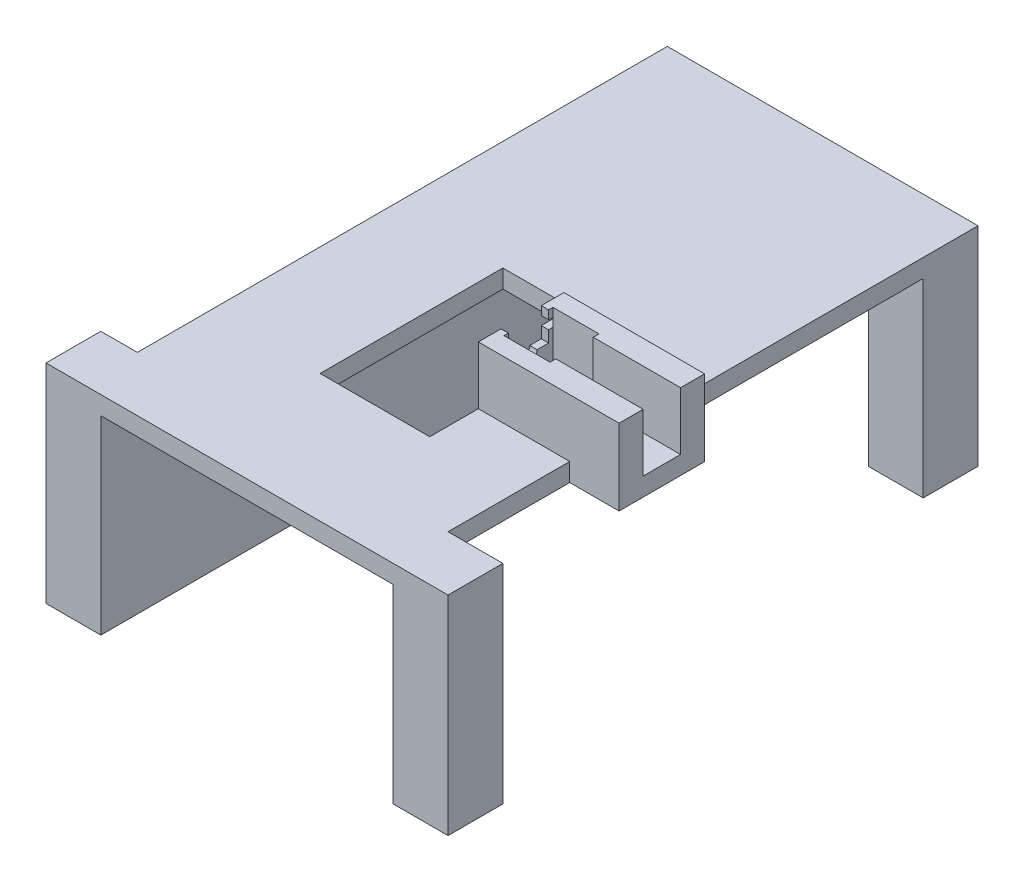
SolidWorks part; units mm, degrees
ref_plane "Front Plane" through (0, 0, 0) normal (0, 0, 1) x (1, 0, 0)
ref_plane "Top Plane" through (0, 0, 0) normal (0, 1, 0) x (1, 0, 0)
ref_plane "Right Plane" through (0, 0, 0) normal (1, 0, 0) x (0, 0, -1)
sketch "Sketch1" plane through (0, 0, 0) normal (0, 1, 0) x (1, 0, 0)
  line L1 (-50.8, -76.2) -> (50.8, -76.2)
  line L2 (-50.8, -76.2) -> (-50.8, 76.2)
  line L3 (-50.8, 76.2) -> (50.8, 76.2)
  line L4 (50.8, -76.2) -> (50.8, 76.2)
  line L5 (-50.8, -76.2) -> (50.8, 76.2) construction
  line L6 (-50.8, 76.2) -> (50.8, -76.2) construction
  point P0 (0, 0)
  dimension "D1" = 152.4
  dimension "D2" = 101.6
extrude "Boss-Extrude1" add sketch "Sketch1" against normal blind 6.35
sketch "Sketch2" plane through (0, 0, 0) normal (0, 1, 0) x (1, 0, 0)
  line L1 (-19.05, -31.75) -> (19.05, -31.75)
  line L2 (-19.05, -31.75) -> (-19.05, 31.75)
  line L3 (-19.05, 31.75) -> (19.05, 31.75)
  line L4 (19.05, -31.75) -> (19.05, 31.75)
  line L5 (-19.05, -31.75) -> (19.05, 31.75) construction
  line L6 (-19.05, 31.75) -> (19.05, -31.75) construction
  point P0 (0, 0)
  dimension "D1" = 38.1
  dimension "D2" = 63.5
extrude "Cut-Extrude1" cut sketch "Sketch2" against normal through all
sketch "Sketch4" plane through (0, 0, 0) normal (0, 1, 0) x (1, 0, 0)
  line L0 (19.05, -31.75) -> (19.05, 31.75) construction
  line L1 (21.59, -8.509) -> (50.8, -8.509)
  line L3 (21.59, 8.509) -> (50.8, 8.509)
  line L4 (50.8, -8.509) -> (50.8, 8.509)
  line L5 (21.59, -8.509) -> (50.8, 8.509) construction
  line L6 (50.8, -8.509) -> (21.59, 8.509) construction
  line L7 (50.8, -76.2) -> (50.8, 76.2) construction
  line L9 (19.05, 14.859) -> (19.05, -14.859)
  line L10 (19.05, 14.859) -> (50.8, 14.859)
  line L11 (50.8, 14.859) -> (50.8, 8.509)
  line L12 (21.59, 8.509) -> (21.59, -8.509)
  line L13 (50.8, 8.509) -> (61.595, 8.509)
  line L14 (19.05, -14.859) -> (50.8, -14.859)
  line L15 (61.595, 8.509) -> (61.595, -8.509)
  line L16 (61.595, -8.509) -> (50.8, -8.509)
  line L17 (50.8, 14.859) -> (67.945, 14.859)
  line L18 (67.945, 14.859) -> (67.945, -14.859)
  line L19 (67.945, -14.859) -> (50.8, -14.859)
  point P0 (19.05, 0)
  point P2 (36.195, 0)
  line M13 (19.05, 31.75) -> (19.05, -31.75)
  line M16 (50.8, -76.2) -> (50.8, 76.2)
  dimension "D1" = 17.018
  dimension "D2" = 6.35
  dimension "D3" = 6.35
  dimension "D4" = 2.54
  dimension "D5" = 40.005
  dimension "D6" = 6.35
extrude "Boss-Extrude3" add sketch "Sketch4" against normal through all and the other way blind 10.0965 contours L19 L18 L17 L13 L15 L16 M16 | L14 L1 L12 L3 L10 M13 M16
sketch "Sketch6" plane through (19.05, 0, 0) normal (-1, 0, 0) x (0, 0, 1)
  line L0 (-14.859, 10.0965) -> (14.859, 10.0965) construction
  circle A0 centre (0, 10.0965) radius 3
  dimension "D1" = 6
extrude "Cut-Extrude2" cut sketch "Sketch6" against normal up to next
sketch "Sketch7" plane through (0, 10.0965, 0) normal (0, 1, 0) x (1, 0, 0)
  line L0 (21.59, 8.509) -> (37.59, 8.509) construction
  line L1 (21.59, 8.509) -> (61.595, 8.509) construction
  line L2 (37.59, 8.509) -> (37.59, 6.5)
  line L3 (37.59, 6.5) -> (61.595, 6.5)
  line L4 (61.595, 8.509) -> (61.595, -8.509) construction
  line L5 (61.595, 6.5) -> (61.595, -6.5)
  line L6 (61.595, -6.5) -> (37.59, -6.5)
  line L7 (37.59, -6.5) -> (37.59, -8.509)
  line L8 (61.595, -8.509) -> (21.59, -8.509) construction
  line L9 (37.59, -8.509) -> (61.595, -8.509)
  line L10 (61.595, -8.509) -> (61.595, -6.5)
  line L11 (61.595, 6.5) -> (61.595, 8.509)
  line L12 (61.595, 8.509) -> (37.59, 8.509)
  line L13 (21.59, 8.509) -> (21.59, 3) construction
  line M8 (21.59, 8.509) -> (61.595, 8.509)
  line M9 (61.595, 8.509) -> (61.595, -8.509)
  dimension "D1" = 13
  dimension "D2" = 16
  dimension "D3" = 24.005
extrude "Boss-Extrude4" add sketch "Sketch7" against normal through all contours L2 L3 M9 M8 | L6 L7 L9 L10
sketch "Sketch10" plane through (50.8, 0, 0) normal (1, 0, 0) x (0, 0, -1)
  line L1 (-6.5, -6.35) -> (6.5, -6.35)
  line L2 (-6.5, -6.35) -> (-6.5, 0)
  line L3 (-6.5, 0) -> (6.5, 0)
  line L4 (6.5, -6.35) -> (6.5, 0)
extrude "Boss-Extrude5" add sketch "Sketch10" along normal through all
sketch "Sketch11" plane through (61.595, 0, 0) normal (-1, 0, 0) x (0, 0, 1)
  line L1 (6.5, 0) -> (-6.5, 0)
  line L2 (6.5, 0) -> (6.5, 10.0965)
  line L3 (6.5, 10.0965) -> (-6.5, 10.0965)
  line L4 (-6.5, 0) -> (-6.5, 10.0965)
extrude "Cut-Extrude3" cut sketch "Sketch11" against normal up to next
sketch "Sketch12" plane through (0, 10.0965, 0) normal (0, 1, 0) x (1, 0, 0)
  line L0 (67.945, -14.859) -> (67.945, -6.5) construction
  line L1 (67.945, -6.5) -> (37.59, -6.5) construction
  line L2 (37.59, -6.5) -> (37.59, -8.509) construction
  line L3 (37.59, -8.509) -> (21.59, -8.509) construction
  line L4 (21.59, -8.509) -> (21.59, -3) construction
  line L5 (21.59, -3) -> (19.05, -3) construction
  line L6 (19.05, -3) -> (19.05, -14.859) construction
  line L7 (19.05, -14.859) -> (67.945, -14.859) construction
  line L8 (37.59, 6.5) -> (67.945, 6.5) construction
  line L9 (67.945, 6.5) -> (67.945, 14.859) construction
  line L10 (67.945, 14.859) -> (19.05, 14.859) construction
  line L11 (19.05, 14.859) -> (19.05, 3) construction
  line L12 (19.05, 3) -> (21.59, 3) construction
  line L13 (21.59, 3) -> (21.59, 8.509) construction
  line L14 (21.59, 8.509) -> (37.59, 8.509) construction
  line L15 (37.59, 8.509) -> (37.59, 6.5) construction
  line L16 (67.945, -14.859) -> (67.945, -6.5)
  line L17 (67.945, -6.5) -> (37.59, -6.5)
  line L18 (37.59, -6.5) -> (37.59, -8.509)
  line L19 (37.59, -8.509) -> (21.59, -8.509)
  line L20 (21.59, -8.509) -> (21.59, -3)
  line L21 (21.59, -3) -> (19.05, -3)
  line L22 (19.05, -3) -> (19.05, -14.859)
  line L23 (19.05, -14.859) -> (67.945, -14.859)
  line L24 (37.59, 6.5) -> (67.945, 6.5)
  line L25 (67.945, 6.5) -> (67.945, 14.859)
  line L26 (67.945, 14.859) -> (19.05, 14.859)
  line L27 (19.05, 14.859) -> (19.05, 3)
  line L28 (19.05, 3) -> (21.59, 3)
  line L29 (21.59, 3) -> (21.59, 8.509)
  line L30 (21.59, 8.509) -> (37.59, 8.509)
  line L31 (37.59, 8.509) -> (37.59, 6.5)
extrude "Boss-Extrude6" add sketch "Sketch12" along normal blind 10
sketch "Sketch13" plane through (19.05, 0, 0) normal (-1, 0, 0) x (0, 0, 1)
  line L0 (3, 10.0965) -> (7, 10.0965)
  line L1 (7, 10.0965) -> (7, 14.0965)
  line L2 (7, 14.0965) -> (11, 14.0965)
  line L3 (11, 14.0965) -> (11, 17.0965)
  line L4 (11, 17.0965) -> (7, 17.0965)
  line L5 (7, 17.0965) -> (7, 20.0965)
  line L6 (3, 20.0965) -> (14.859, 20.0965) construction
  line L7 (7, 20.0965) -> (3, 20.0965)
  line L8 (3, 20.0965) -> (3, 10.0965)
  arc A0 (-3, 10.0965) -> (3, 10.0965) centre (0, 10.0965) ccw construction
  arc A1 (-3, 10.0965) -> (3, 10.0965) centre (0, 10.0965) ccw construction
  dimension "D1" = 4
  dimension "D2" = 4
  dimension "D3" = 3
  dimension "D4" = 4
extrude "Cut-Extrude4" cut sketch "Sketch13" against normal up to surface (2.54 mm away) up to face at (21.59, 12.1974, 0)
mirror "Mirror1" about plane through (0, 0, 0) normal (0, 0, 1) of "Cut-Extrude4"
sketch "Sketch14" plane through (0, 0, -76.2) normal (0, 0, -1) x (-1, 0, 0)
  line L4 (50.8, 0) -> (-50.8, 0)
  line L5 (-50.8, 0) -> (-50.8, -6.35)
  line L6 (-50.8, -6.35) -> (50.8, -6.35)
  line L7 (50.8, -6.35) -> (50.8, 0)
  line L8 (50.8, 0) -> (-50.8, 0)
  line L9 (-50.8, 0) -> (-50.8, -6.35)
  line L10 (-50.8, -6.35) -> (50.8, -6.35)
  line L11 (50.8, -6.35) -> (50.8, 0)
  dimension "D1" = 0
extrude "Boss-Extrude7" add sketch "Sketch14" along normal blind 50.8
sketch "Sketch15" plane through (0, -6.35, 0) normal (0, -1, 0) x (1, 0, 0)
  line L1 (-69.85, 76.2) -> (-50.8, 76.2)
  line L2 (-69.85, 76.2) -> (-69.85, 57.15)
  line L3 (-69.85, 57.15) -> (-50.8, 57.15)
  line L4 (-50.8, 76.2) -> (-50.8, 57.15)
  line L5 (69.85, 76.2) -> (50.8, 76.2)
  line L6 (69.85, 76.2) -> (69.85, 57.15)
  line L7 (69.85, 57.15) -> (50.8, 57.15)
  line L8 (50.8, 76.2) -> (50.8, 57.15)
  line L9 (-50.8, -127) -> (-31.75, -127)
  line L10 (-50.8, -127) -> (-50.8, -107.95)
  line L11 (-50.8, -107.95) -> (-31.75, -107.95)
  line L12 (-31.75, -127) -> (-31.75, -107.95)
  line L13 (50.8, -127) -> (31.75, -127)
  line L14 (50.8, -127) -> (50.8, -107.95)
  line L15 (50.8, -107.95) -> (31.75, -107.95)
  line L16 (31.75, -127) -> (31.75, -107.95)
  point P20 (0, 0)
  point P21 (0, 0)
  dimension "D1" = 19.05
  dimension "D2" = 19.05
  dimension "D3" = 19.05
  dimension "D4" = 19.05
  dimension "D5" = 19.05
extrude "Boss-Extrude8" add sketch "Sketch15" along normal blind 66.04
sketch "Sketch16" plane through (0, -6.35, 0) normal (0, 1, 0) x (1, 0, 0)
  line L0 (69.85, -76.2) -> (69.85, -57.15) construction
  line L1 (69.85, -57.15) -> (50.8, -57.15) construction
  line L2 (50.8, -57.15) -> (50.8, -76.2) construction
  line L3 (50.8, -76.2) -> (69.85, -76.2) construction
  line L4 (-69.85, -57.15) -> (-69.85, -76.2) construction
  line L5 (-69.85, -76.2) -> (-50.8, -76.2) construction
  line L6 (-50.8, -76.2) -> (-50.8, -57.15) construction
  line L7 (-50.8, -57.15) -> (-69.85, -57.15) construction
  line L8 (69.85, -76.2) -> (69.85, -57.15)
  line L9 (69.85, -57.15) -> (50.8, -57.15)
  line L10 (50.8, -57.15) -> (50.8, -76.2)
  line L11 (50.8, -76.2) -> (69.85, -76.2)
  line L12 (-69.85, -57.15) -> (-69.85, -76.2)
  line L13 (-69.85, -76.2) -> (-50.8, -76.2)
  line L14 (-50.8, -76.2) -> (-50.8, -57.15)
  line L15 (-50.8, -57.15) -> (-69.85, -57.15)
extrude "Boss-Extrude9" add sketch "Sketch16" along normal up to surface (6.35 mm away) up to face at (11.6417, 0, -8.4667)
sketch "Sketch17" plane through (-50.8, 0, 0) normal (-1, 0, 0) x (0, 0, 1)
  line L1 (-127, 0) -> (57.15, 0)
  line L2 (-127, 0) -> (-127, -72.39)
  line L3 (-127, -72.39) -> (57.15, -72.39)
  line L4 (57.15, 0) -> (57.15, -72.39)
extrude "Boss-Extrude10" add sketch "Sketch17" along normal blind 6.35
